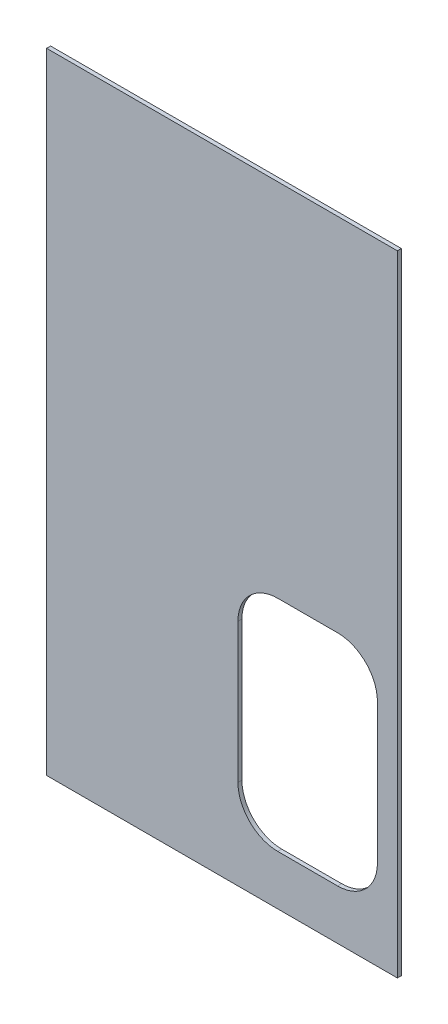
SolidWorks part; units mm, degrees
ref_plane "Plan de face" through (0, 0, 0) normal (0, 0, 1) x (1, 0, 0)
ref_plane "Plan de dessus" through (0, 0, 0) normal (0, 1, 0) x (1, 0, 0)
ref_plane "Plan de droite" through (0, 0, 0) normal (1, 0, 0) x (0, 0, -1)
sketch "Esquisse1" plane through (0, 0, 0) normal (0, 0, 1) x (1, 0, 0)
  line L1 (0, 0) -> (176, 0)
  line L2 (0, 0) -> (0, 316)
  line L3 (0, 316) -> (176, 316)
  line L4 (176, 0) -> (176, 316)
  line L5 (166, 25) -> (96, 25)
  line L6 (166, 25) -> (166, 135)
  line L7 (166, 135) -> (96, 135)
  line L8 (96, 25) -> (96, 135)
  point P9 (137.7535, 135)
  dimension "D1" = 316
  dimension "D2" = 176
  dimension "D3" = 25
  dimension "D4" = 135
  dimension "D5" = 70
  dimension "D6" = 10
extrude "Boss.-Extru.1" add sketch "Esquisse1" along normal blind 2
fillet "Congé1" radius 20 4 edges at (96, 135, 1) (166, 135, 1) (166, 25, 1) (96, 25, 1)
